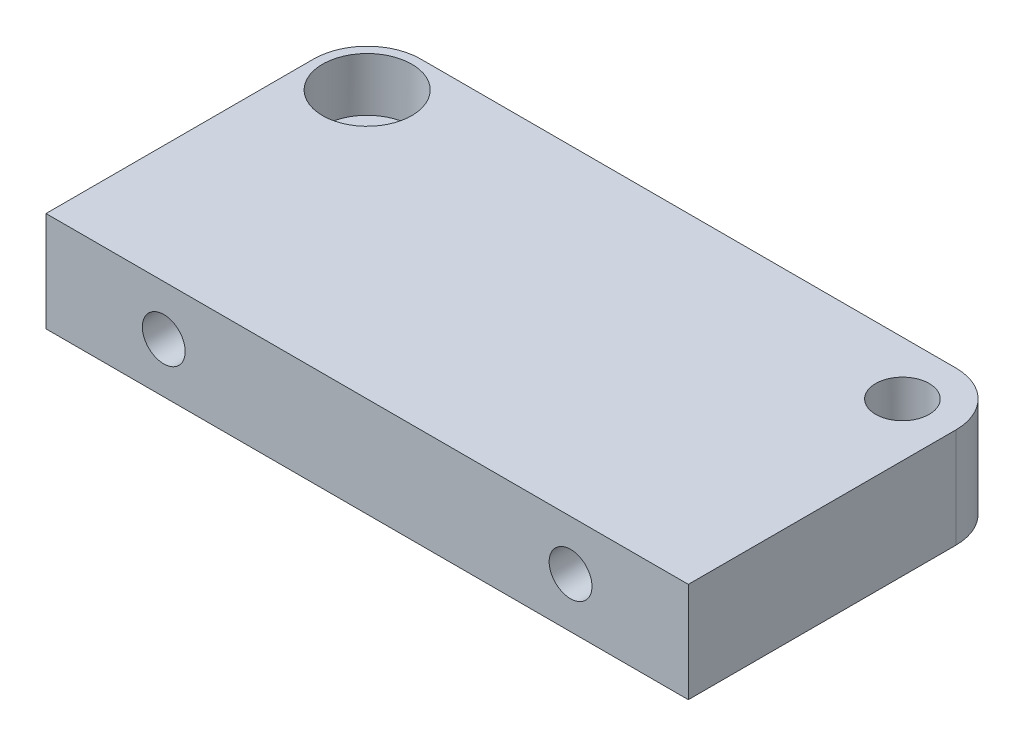
SolidWorks part; units mm, degrees
ref_plane "前视基准面" through (0, 0, 0) normal (0, 0, 1) x (1, 0, 0)
ref_plane "上视基准面" through (0, 0, 0) normal (0, 1, 0) x (1, 0, 0)
ref_plane "右视基准面" through (0, 0, 0) normal (1, 0, 0) x (0, 0, -1)
sketch "草图1" plane through (0, 0, 0) normal (0, 0, 1) x (1, 0, 0)
  line L1 (0, 0) -> (180, 0)
  line L2 (0, 0) -> (0, -28)
  line L3 (0, -28) -> (180, -28)
  line L4 (180, 0) -> (180, -28)
  dimension "D1" = 180
  dimension "D2" = 28
extrude "拉伸1" add sketch "草图1" along normal blind 90
sketch "草图2" plane through (0, 0, 90) normal (0, 0, 1) x (1, 0, 0)
  line L0 (180, 0) -> (0, 0) construction
  circle A0 centre (33, -14) radius 6
  circle A1 centre (147, -14) radius 6
  dimension "D1" = 14
  dimension "D2" = 14
extrude "切除-拉伸1" cut sketch "草图2" against normal blind 60
sketch "草图3" plane through (0, 0, 0) normal (0, 1, 0) x (1, 0, 0)
  line L0 (0, -90) -> (0, 0) construction
  line L1 (180, 0) -> (0, 0) construction
  circle A0 centre (15, -15) radius 12.5
  circle A1 centre (165, -15) radius 7.5
  dimension "D1" = 25
  dimension "D2" = 15
  dimension "D3" = 15
  dimension "D4" = 150
extrude "切除-拉伸2" cut sketch "草图3" against normal blind 30
fillet "圆角1" radius 15 2 edges at (180, -14, 0) (0, -14, 0)
sketch "草图4" plane through (0, -28, 0) normal (0, -1, 0) x (1, 0, 0)
  circle A0 centre (15, 15) radius 12.5
  circle A1 centre (15, 15) radius 7
extrude "拉伸2" add sketch "草图4" against normal blind 13
